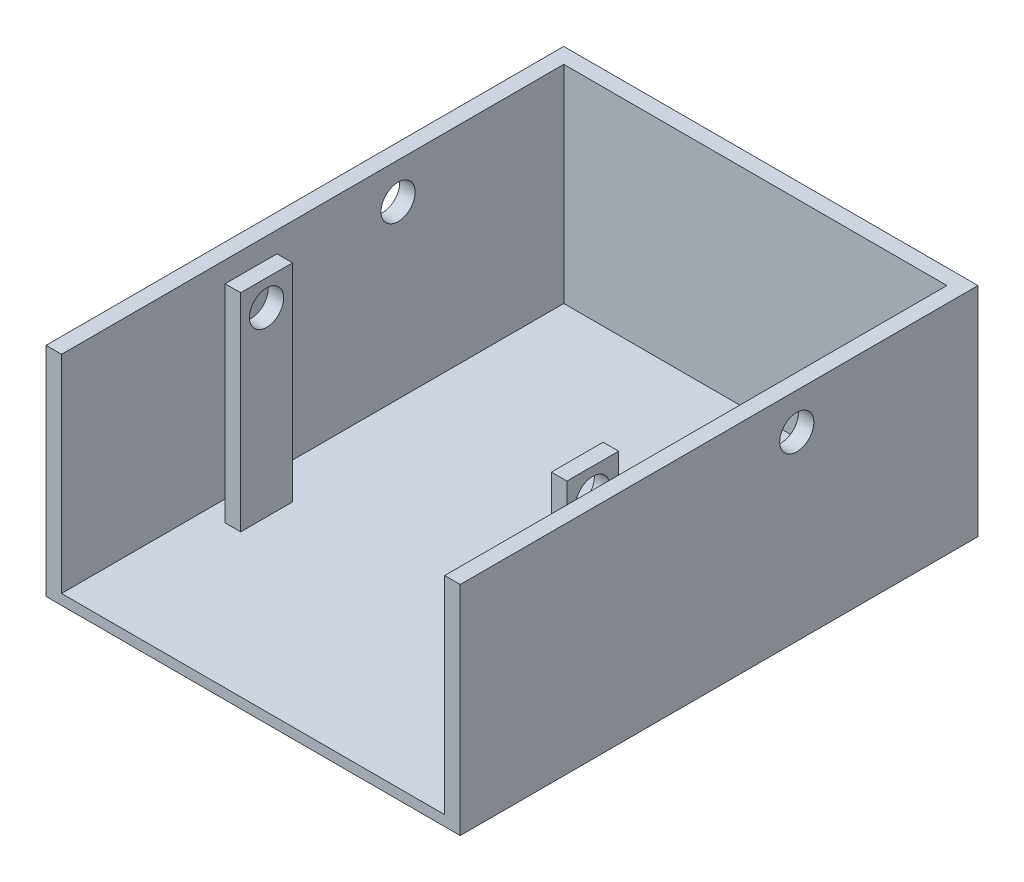
SolidWorks part; units mm, degrees
ref_plane "Front Plane" through (0, 0, 0) normal (0, 0, 1) x (1, 0, 0)
ref_plane "Top Plane" through (0, 0, 0) normal (0, 1, 0) x (1, 0, 0)
ref_plane "Right Plane" through (0, 0, 0) normal (1, 0, 0) x (0, 0, -1)
sketch "Sketch3" plane through (0, 0, 0) normal (0, 1, 0) x (1, 0, 0)
  line L1 (-200, 250) -> (200, 250)
  line L2 (-200, 250) -> (-200, -250)
  line L3 (-200, -250) -> (200, -250)
  line L4 (200, 250) -> (200, -250)
  line L5 (-200, 250) -> (200, -250) construction
  line L6 (-200, -250) -> (200, 250) construction
  point P0 (0, 0)
  dimension "D1" = 400
  dimension "D2" = 500
extrude "Boss-Extrude1" add sketch "Sketch3" along normal blind 10
sketch "Sketch4" plane through (0, 10, 0) normal (0, 1, 0) x (1, 0, 0)
  line L0 (-185, -235) -> (-185, -250)
  line L1 (-200, 250) -> (200, 250)
  line L2 (-200, 250) -> (-200, -250)
  line L3 (-200, -250) -> (200, -250)
  line L4 (200, 250) -> (200, -250)
  line L5 (-200, 250) -> (200, -250) construction
  line L6 (-200, -250) -> (200, 250) construction
  line L7 (-185, 235) -> (185, 235)
  line L8 (-185, 235) -> (-185, -235)
  line L10 (185, 235) -> (185, -235)
  line L11 (-185, 235) -> (185, -235) construction
  line L12 (-185, -235) -> (185, 235) construction
  line L13 (185, -235) -> (185, -250)
  line L14 (-185, -250) -> (-200, -250)
  line L15 (185, -250) -> (200, -250)
  point P0 (0, 0)
  point P7 (0, 0)
  line M9 (200, -250) -> (200, 250)
  line M10 (200, 250) -> (-200, 250)
  line M11 (-200, 250) -> (-200, -250)
  line M12 (-200, -250) -> (200, -250)
  dimension "D1" = 15
  dimension "D2" = 15
  dimension "D3" = 15
extrude "Boss-Extrude3" add sketch "Sketch4" along normal blind 200 contours L10 L13 L3 L0 L8 L7 M9 M10 M11 M12
sketch "Sketch5" plane through (-200, 0, 0) normal (-1, 0, 0) x (0, 0, 1)
  line L0 (-250, 210) -> (-250, 0) construction
  line L1 (-250, 0) -> (250, 0) construction
  circle A0 centre (-75, 175) radius 16.5
  dimension "D1" = 33
  dimension "D3" = 175
  dimension "D2" = 175
extrude "Cut-Extrude1" cut sketch "Sketch5" against normal through all both and the other way through all
sketch "Sketch6" plane through (0, 10, 0) normal (0, 1, 0) x (1, 0, 0)
  line L0 (200, 250) -> (-200, 250) construction
  line L1 (-165, -62) -> (-150, -62)
  line L2 (-165, -62) -> (-165, -112)
  line L3 (-165, -112) -> (-150, -112)
  line L4 (-150, -62) -> (-150, -112)
  line L5 (-165, -62) -> (-150, -112) construction
  line L6 (-165, -112) -> (-150, -62) construction
  line L7 (150, -62) -> (165, -62)
  line L8 (150, -62) -> (150, -112)
  line L9 (150, -112) -> (165, -112)
  line L10 (165, -62) -> (165, -112)
  line L11 (150, -62) -> (165, -112) construction
  line L12 (150, -112) -> (165, -62) construction
  line L13 (-185, 235) -> (-185, -250) construction
  point P0 (-157.5, -87)
  point P5 (157.5, -87)
  point P12 (-157.5, -62)
  dimension "D1" = 15
  dimension "D2" = 50
  dimension "D3" = 312
  dimension "D4" = 20
  dimension "D5" = 330
extrude "Boss-Extrude4" add sketch "Sketch6" along normal blind 200
sketch "Sketch9" plane through (-150, 0, 0) normal (1, 0, 0) x (0, 0, -1)
  line L0 (-87, 210) -> (-87, 185) construction
  line L1 (-112, 210) -> (-62, 210) construction
  line L2 (-112, 10) -> (-62, 10) construction
  circle A0 centre (-87, 185) radius 16.5
  dimension "D1" = 33
  dimension "D2" = 175
extrude "Cut-Extrude3" cut sketch "Sketch9" against normal blind 15
sketch "Sketch10" plane through (165, 0, 0) normal (1, 0, 0) x (0, 0, -1)
  line L0 (-87, 185) -> (-87, 210) construction
  line L2 (-112, 10) -> (-62, 10) construction
  line L4 (-112, 210) -> (-62, 210) construction
  circle A0 centre (-87, 185) radius 16.5
  dimension "D1" = 33
  dimension "D2" = 175
extrude "Cut-Extrude4" cut sketch "Sketch10" against normal blind 15
